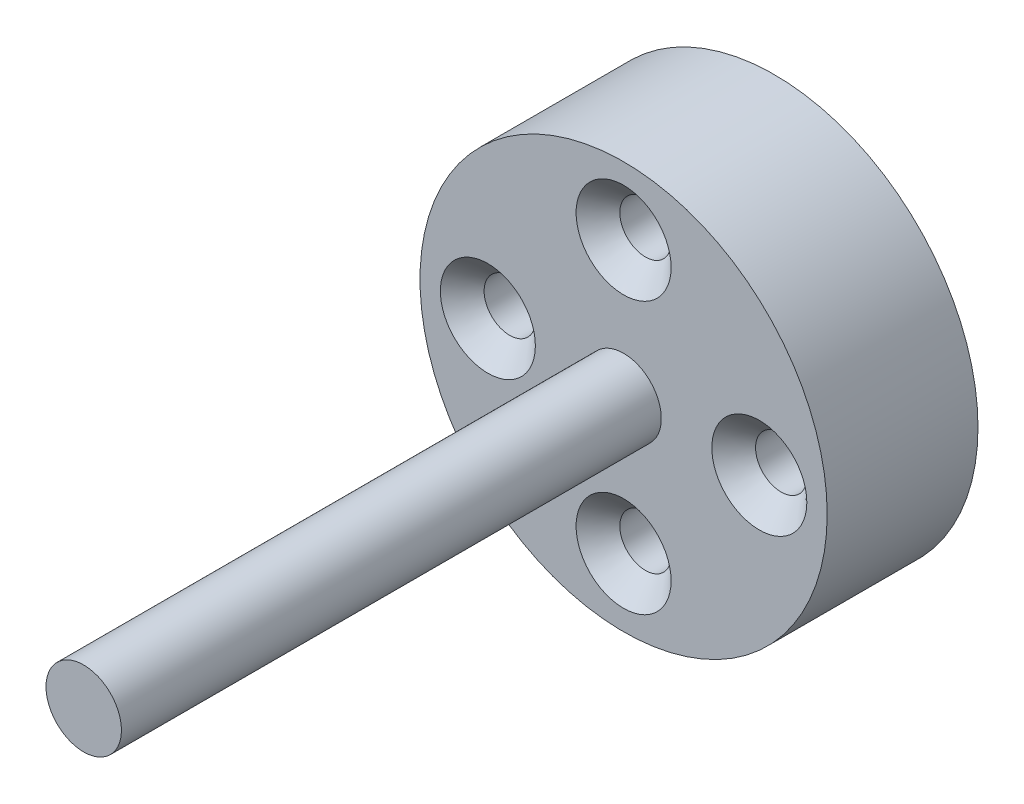
SolidWorks part; units mm, degrees
ref_plane "Front Plane" through (0, 0, 0) normal (0, 0, 1) x (1, 0, 0)
ref_plane "Top Plane" through (0, 0, 0) normal (0, 1, 0) x (1, 0, 0)
ref_plane "Right Plane" through (0, 0, 0) normal (1, 0, 0) x (0, 0, -1)
sketch "Sketch1" plane through (0, 0, 0) normal (0, 0, 1) x (1, 0, 0)
  circle A0 centre (0, 0) radius 13.5
  circle A1 centre (0, 0) radius 9
  circle A2 centre (0, 9) radius 1.6
  circle A3 centre (0, -9) radius 1.6
  circle A4 centre (-9, 0) radius 1.6
  circle A5 centre (9, 0) radius 1.6
  dimension "D1" = 27
  dimension "D2" = 18
  dimension "D3" = 3.2
  dimension "D4" = 3.2
  dimension "D5" = 3.2
  dimension "D6" = 3.2
extrude "Boss-Extrude1" add sketch "Sketch1" along normal blind 10 contours A0 A5 A1 A3 A4 A2 | A5 A1 A2 A4 A3
sketch "Sketch2" plane through (0, 0, 10) normal (0, 0, 1) x (1, 0, 0)
  circle A0 centre (0, 0) radius 2.5
  dimension "D1" = 5
extrude "Boss-Extrude2" add sketch "Sketch2" along normal blind 35.8
sketch "Sketch3" plane through (0, 0, 0) normal (0, 0, -1) x (-1, 0, 0)
  circle A0 centre (0, 0) radius 2.3
  dimension "D1" = 4.6
extrude "Cut-Extrude1" cut sketch "Sketch3" against normal blind 6
hole_wizard "CSK for M3 Flat Head Machine Screw1" positions "Sketch5" profile "Sketch6" countersink size "M3" standard "ANSI Metric"
sketch "Sketch5" plane through (0, 0, 10) normal (0, 0, 1) x (1, 0, 0)
  point P0 (0, 9)
  point P3 (9, 0)
  point P6 (-9, 0)
  point P9 (0, -9)
sketch "Sketch6" plane through (0, 9, 10) normal (1, 0, 0) x (0, -1, 0)
  line L0 (0, 0) -> (0, 11.0205)
  line L1 (0, 11.0205) -> (1.7, 9.999)
  line L2 (1.7, 9.999) -> (1.7, 1.45)
  line L3 (1.7, 1.45) -> (3.15, 0)
  line L5 (3.15, 0) -> (0, 0)
  line L6 (-1.7, 1.45) -> (-3.15, 0) construction
  line L10 (0, 11.0205) -> (-1.7, 9.999) construction
  line L11 (0, -6.35) -> (0, 107.95) construction
  dimension "Hole Dia." = 3.4
  dimension "Hole Depth" = 9.999
  dimension "Near C'Sink Dia." = 6.3
  dimension "Near C'Sink Angle" = 90
  dimension "Drill Angle" = 118
